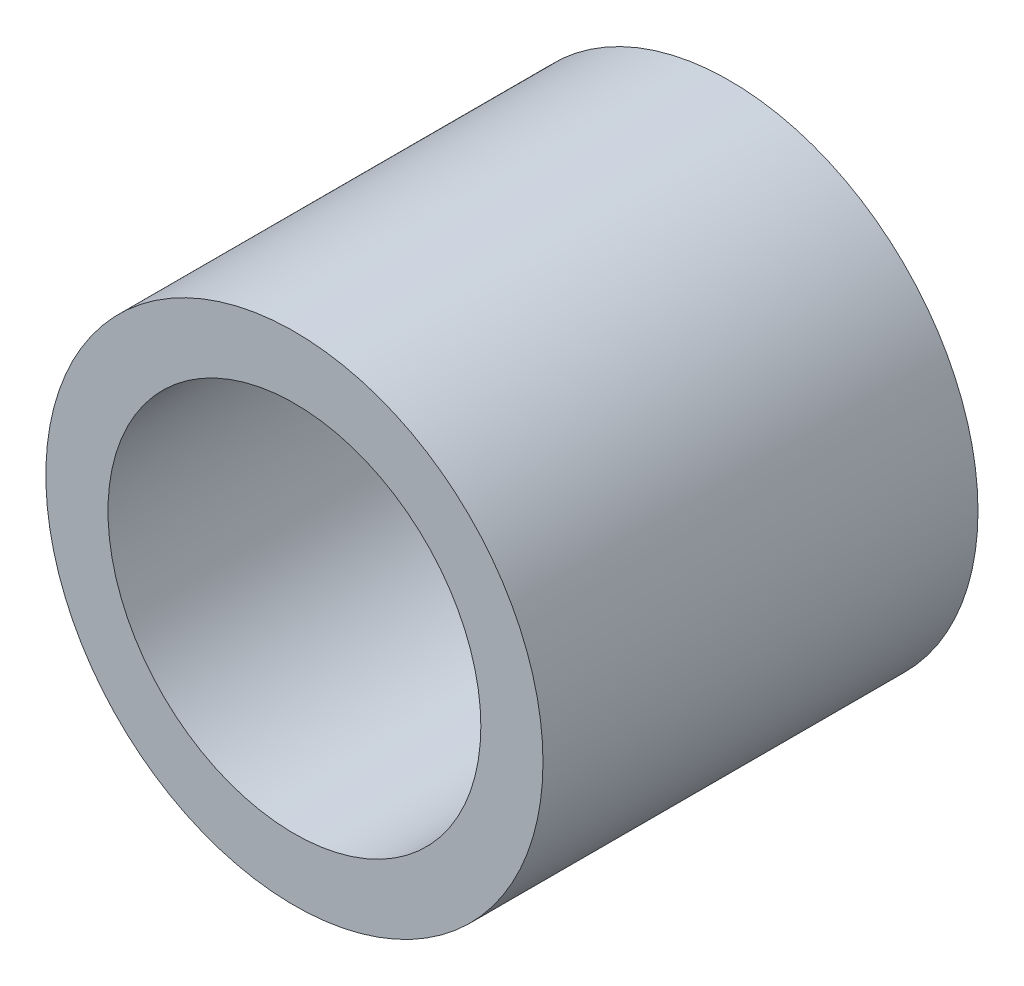
SolidWorks part; units mm, degrees
ref_plane "Front Plane" through (0, 0, 0) normal (0, 0, 1) x (1, 0, 0)
ref_plane "Top Plane" through (0, 0, 0) normal (0, 1, 0) x (1, 0, 0)
ref_plane "Right Plane" through (0, 0, 0) normal (1, 0, 0) x (0, 0, -1)
sketch "Sketch1" plane through (0, 0, 0) normal (0, 0, 1) x (1, 0, 0)
  circle A0 centre (0, 0) radius 20
  circle A1 centre (0, 0) radius 15
  dimension "D1" = 40
  dimension "D2" = 30
extrude "Boss-Extrude1" add sketch "Sketch1" along normal mid plane 35
